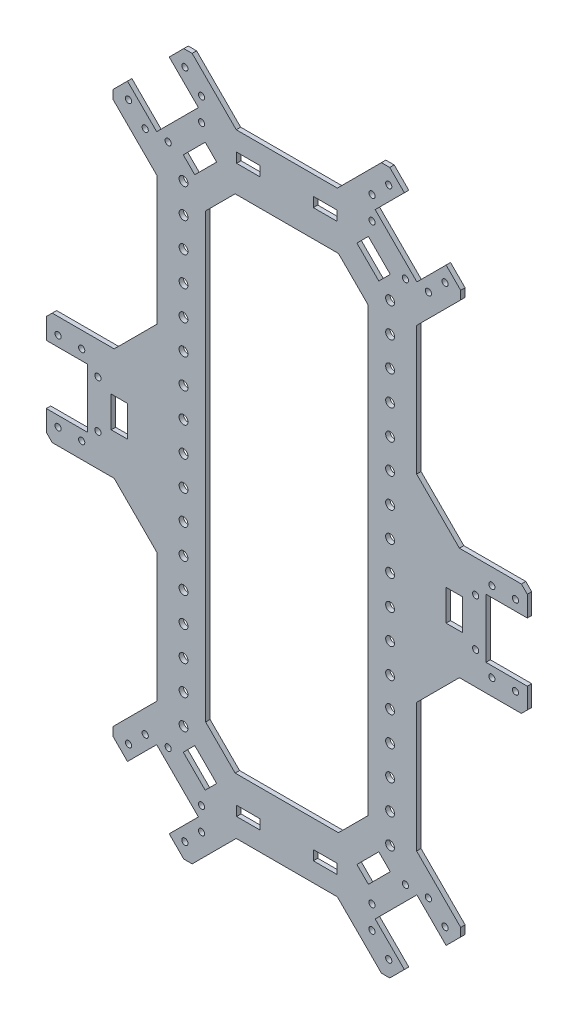
SolidWorks part; units mm, degrees
ref_plane "Спереди" through (0, 0, 0) normal (0, 0, 1) x (1, 0, 0)
ref_plane "Сверху" through (0, 0, 0) normal (0, 1, 0) x (1, 0, 0)
ref_plane "Справа" through (0, 0, 0) normal (1, 0, 0) x (0, 0, -1)
sketch "Model" plane through (0, 0, 0) normal (0, 0, 1) x (1, 0, 0)
  line L0 (-64, 8) -> (-60.95, 8) construction
  line L1 (-64, 8) -> (-67.05, 8) construction
  line L2 (-64, 8) -> (-64, 11.05) construction
  line L3 (-64, 8) -> (-64, 4.95) construction
  line L4 (-64, -8) -> (-60.95, -8) construction
  line L5 (-64, -8) -> (-67.05, -8) construction
  line L6 (-64, -8) -> (-64, -4.95) construction
  line L7 (-64, -8) -> (-64, -11.05) construction
  line L8 (-69.5, 13.5) -> (-66.45, 13.5) construction
  line L9 (-69.5, 13.5) -> (-72.55, 13.5) construction
  line L10 (-69.5, 13.5) -> (-69.5, 16.55) construction
  line L11 (-69.5, 13.5) -> (-69.5, 10.45) construction
  line L12 (-69.5, -13.5) -> (-66.45, -13.5) construction
  line L13 (-69.5, -13.5) -> (-72.55, -13.5) construction
  line L14 (-69.5, -13.5) -> (-69.5, -10.45) construction
  line L15 (-69.5, -13.5) -> (-69.5, -16.55) construction
  line L16 (-40.201, -88.8873) -> (-38.0443, -86.7306) construction
  line L17 (-40.201, -88.8873) -> (-42.3577, -91.044) construction
  line L18 (-40.201, -88.8873) -> (-42.3577, -86.7306) construction
  line L19 (-40.201, -88.8873) -> (-38.0443, -91.044) construction
  line L20 (-28.8873, -100.201) -> (-26.7306, -98.0443) construction
  line L21 (-28.8873, -100.201) -> (-31.044, -102.3577) construction
  line L22 (-28.8873, -100.201) -> (-31.044, -98.0443) construction
  line L23 (-28.8873, -100.201) -> (-26.7306, -102.3577) construction
  line L24 (-53.636, -94.5442) -> (-51.4794, -92.3875) construction
  line L25 (-53.636, -94.5442) -> (-55.7927, -96.7008) construction
  line L26 (-53.636, -94.5442) -> (-55.7927, -92.3875) construction
  line L27 (-53.636, -94.5442) -> (-51.4794, -96.7008) construction
  line L28 (-47.9792, -88.8873) -> (-45.8225, -86.7306) construction
  line L29 (-47.9792, -88.8873) -> (-50.1359, -91.044) construction
  line L30 (-47.9792, -88.8873) -> (-50.1359, -86.7306) construction
  line L31 (-47.9792, -88.8873) -> (-45.8225, -91.044) construction
  line L32 (-28.8873, -107.9792) -> (-26.7306, -105.8225) construction
  line L33 (-28.8873, -107.9792) -> (-31.044, -110.1359) construction
  line L34 (-28.8873, -107.9792) -> (-31.044, -105.8225) construction
  line L35 (-28.8873, -107.9792) -> (-26.7306, -110.1359) construction
  line L36 (-34.5442, -113.636) -> (-32.3875, -111.4794) construction
  line L37 (-34.5442, -113.636) -> (-36.7008, -115.7927) construction
  line L38 (-34.5442, -113.636) -> (-36.7008, -111.4794) construction
  line L39 (-34.5442, -113.636) -> (-32.3875, -115.7927) construction
  line L40 (-77.5, 13.5) -> (-74.45, 13.5) construction
  line L41 (-77.5, 13.5) -> (-80.55, 13.5) construction
  line L42 (-77.5, 13.5) -> (-77.5, 16.55) construction
  line L43 (-77.5, 13.5) -> (-77.5, 10.45) construction
  line L44 (-77.5, -13.5) -> (-74.45, -13.5) construction
  line L45 (-77.5, -13.5) -> (-80.55, -13.5) construction
  line L46 (-77.5, -13.5) -> (-77.5, -10.45) construction
  line L47 (-77.5, -13.5) -> (-77.5, -16.55) construction
  line L48 (-40.201, 88.8873) -> (-38.0443, 86.7306) construction
  line L49 (-40.201, 88.8873) -> (-42.3577, 91.044) construction
  line L50 (-40.201, 88.8873) -> (-42.3577, 86.7306) construction
  line L51 (-40.201, 88.8873) -> (-38.0443, 91.044) construction
  line L52 (-28.8873, 100.201) -> (-26.7306, 98.0443) construction
  line L53 (-28.8873, 100.201) -> (-31.044, 102.3577) construction
  line L54 (-28.8873, 100.201) -> (-31.044, 98.0443) construction
  line L55 (-28.8873, 100.201) -> (-26.7306, 102.3577) construction
  line L56 (-53.636, 94.5442) -> (-51.4794, 92.3875) construction
  line L57 (-53.636, 94.5442) -> (-55.7927, 96.7008) construction
  line L58 (-53.636, 94.5442) -> (-55.7927, 92.3875) construction
  line L59 (-53.636, 94.5442) -> (-51.4794, 96.7008) construction
  line L60 (-47.9792, 88.8873) -> (-45.8225, 86.7306) construction
  line L61 (-47.9792, 88.8873) -> (-50.1359, 91.044) construction
  line L62 (-47.9792, 88.8873) -> (-50.1359, 86.7306) construction
  line L63 (-47.9792, 88.8873) -> (-45.8225, 91.044) construction
  line L64 (-28.8873, 107.9792) -> (-26.7306, 105.8225) construction
  line L65 (-28.8873, 107.9792) -> (-31.044, 110.1359) construction
  line L66 (-28.8873, 107.9792) -> (-31.044, 105.8225) construction
  line L67 (-28.8873, 107.9792) -> (-26.7306, 110.1359) construction
  line L68 (-34.5442, 113.636) -> (-32.3875, 111.4794) construction
  line L69 (-34.5442, 113.636) -> (-36.7008, 115.7927) construction
  line L70 (-34.5442, 113.636) -> (-36.7008, 111.4794) construction
  line L71 (-34.5442, 113.636) -> (-32.3875, 115.7927) construction
  line L72 (64, 8) -> (60.95, 8) construction
  line L73 (64, 8) -> (67.05, 8) construction
  line L74 (64, 8) -> (64, 11.05) construction
  line L75 (64, 8) -> (64, 4.95) construction
  line L76 (64, -8) -> (60.95, -8) construction
  line L77 (64, -8) -> (67.05, -8) construction
  line L78 (64, -8) -> (64, -4.95) construction
  line L79 (64, -8) -> (64, -11.05) construction
  line L80 (69.5, 13.5) -> (66.45, 13.5) construction
  line L81 (69.5, 13.5) -> (72.55, 13.5) construction
  line L82 (69.5, 13.5) -> (69.5, 16.55) construction
  line L83 (69.5, 13.5) -> (69.5, 10.45) construction
  line L84 (69.5, -13.5) -> (66.45, -13.5) construction
  line L85 (69.5, -13.5) -> (72.55, -13.5) construction
  line L86 (69.5, -13.5) -> (69.5, -10.45) construction
  line L87 (69.5, -13.5) -> (69.5, -16.55) construction
  line L88 (40.201, -88.8873) -> (38.0443, -86.7306) construction
  line L89 (40.201, -88.8873) -> (42.3577, -91.044) construction
  line L90 (40.201, -88.8873) -> (42.3577, -86.7306) construction
  line L91 (40.201, -88.8873) -> (38.0443, -91.044) construction
  line L92 (28.8873, -100.201) -> (26.7306, -98.0443) construction
  line L93 (28.8873, -100.201) -> (31.044, -102.3577) construction
  line L94 (28.8873, -100.201) -> (31.044, -98.0443) construction
  line L95 (28.8873, -100.201) -> (26.7306, -102.3577) construction
  line L96 (53.636, -94.5442) -> (51.4794, -92.3875) construction
  line L97 (53.636, -94.5442) -> (55.7927, -96.7008) construction
  line L98 (53.636, -94.5442) -> (55.7927, -92.3875) construction
  line L99 (53.636, -94.5442) -> (51.4794, -96.7008) construction
  line L100 (47.9792, -88.8873) -> (45.8225, -86.7306) construction
  line L101 (47.9792, -88.8873) -> (50.1359, -91.044) construction
  line L102 (47.9792, -88.8873) -> (50.1359, -86.7306) construction
  line L103 (47.9792, -88.8873) -> (45.8225, -91.044) construction
  line L104 (28.8873, -107.9792) -> (26.7306, -105.8225) construction
  line L105 (28.8873, -107.9792) -> (31.044, -110.1359) construction
  line L106 (28.8873, -107.9792) -> (31.044, -105.8225) construction
  line L107 (28.8873, -107.9792) -> (26.7306, -110.1359) construction
  line L108 (34.5442, -113.636) -> (32.3875, -111.4794) construction
  line L109 (34.5442, -113.636) -> (36.7008, -115.7927) construction
  line L110 (34.5442, -113.636) -> (36.7008, -111.4794) construction
  line L111 (34.5442, -113.636) -> (32.3875, -115.7927) construction
  line L112 (77.5, 13.5) -> (74.45, 13.5) construction
  line L113 (77.5, 13.5) -> (80.55, 13.5) construction
  line L114 (77.5, 13.5) -> (77.5, 16.55) construction
  line L115 (77.5, 13.5) -> (77.5, 10.45) construction
  line L116 (77.5, -13.5) -> (74.45, -13.5) construction
  line L117 (77.5, -13.5) -> (80.55, -13.5) construction
  line L118 (77.5, -13.5) -> (77.5, -10.45) construction
  line L119 (77.5, -13.5) -> (77.5, -16.55) construction
  line L120 (40.201, 88.8873) -> (38.0443, 86.7306) construction
  line L121 (40.201, 88.8873) -> (42.3577, 91.044) construction
  line L122 (40.201, 88.8873) -> (42.3577, 86.7306) construction
  line L123 (40.201, 88.8873) -> (38.0443, 91.044) construction
  line L124 (28.8873, 100.201) -> (26.7306, 98.0443) construction
  line L125 (28.8873, 100.201) -> (31.044, 102.3577) construction
  line L126 (28.8873, 100.201) -> (31.044, 98.0443) construction
  line L127 (28.8873, 100.201) -> (26.7306, 102.3577) construction
  line L128 (53.636, 94.5442) -> (51.4794, 92.3875) construction
  line L129 (53.636, 94.5442) -> (55.7927, 96.7008) construction
  line L130 (53.636, 94.5442) -> (55.7927, 92.3875) construction
  line L131 (53.636, 94.5442) -> (51.4794, 96.7008) construction
  line L132 (47.9792, 88.8873) -> (45.8225, 86.7306) construction
  line L133 (47.9792, 88.8873) -> (50.1359, 91.044) construction
  line L134 (47.9792, 88.8873) -> (50.1359, 86.7306) construction
  line L135 (47.9792, 88.8873) -> (45.8225, 91.044) construction
  line L136 (28.8873, 107.9792) -> (26.7306, 105.8225) construction
  line L137 (28.8873, 107.9792) -> (31.044, 110.1359) construction
  line L138 (28.8873, 107.9792) -> (31.044, 105.8225) construction
  line L139 (28.8873, 107.9792) -> (26.7306, 110.1359) construction
  line L140 (34.5442, 113.636) -> (32.3875, 111.4794) construction
  line L141 (34.5442, 113.636) -> (36.7008, 115.7927) construction
  line L142 (34.5442, 113.636) -> (36.7008, 111.4794) construction
  line L143 (34.5442, 113.636) -> (32.3875, 115.7927) construction
  line L144 (27.5, -60) -> (-27.5, -60) construction
  line L145 (-17.1299, 104) -> (17.1299, 104)
  line L146 (0, 106) -> (0, -106) construction
  line L147 (-27.5, 0) -> (-27.5, 75)
  line L148 (-17.5, 85) -> (0, 85)
  line L149 (17.5, 85) -> (0, 85)
  line L150 (-27.5, 0) -> (-27.5, -75)
  line L151 (-17.5, -85) -> (0, -85)
  line L152 (17.5, -85) -> (0, -85)
  line L153 (-17.5, -85) -> (-27.5, -75)
  line L154 (-27.5, 75) -> (-17.5, 85)
  line L155 (-67.5, 10) -> (-67.5, -10)
  line L156 (-58.5, 19) -> (-79.5, 19)
  line L157 (2, 0) -> (-69.5, 0) construction
  line L158 (-2, 0) -> (69.5, 0) construction
  line L159 (27.5, 0) -> (-27.5, 0) construction
  line L160 (-53.9896, -99.8475) -> (-44.0901, -89.948)
  line L161 (-44.0901, -89.948) -> (-29.948, -104.0901)
  line L162 (-29.948, -104.0901) -> (-39.8475, -113.9896)
  line L163 (-53.9896, -99.8475) -> (-58.9393, -94.8977)
  line L164 (-39.8475, -113.9896) -> (-34.8977, -118.9393)
  line L165 (-44, -77.1299) -> (-58.9393, -92.0693)
  line L166 (-58.9393, -94.8977) -> (-58.9393, -92.0693)
  line L167 (-17.1299, -104) -> (-32.0693, -118.9393)
  line L168 (-34.8977, -118.9393) -> (-32.0693, -118.9393)
  line L169 (-38.4332, -98.4332) -> (1.4142, -58.5858) construction
  line L170 (38.4332, -98.4332) -> (-1.4142, -58.5858) construction
  line L171 (-17.1299, -104) -> (17.1299, -104)
  line L172 (-81.5, 10) -> (-67.5, 10)
  line L173 (-67.5, -10) -> (-81.5, -10)
  line L174 (-81.5, 10) -> (-81.5, 17)
  line L175 (-81.5, -10) -> (-81.5, -17)
  line L176 (-81.5, 17) -> (-79.5, 19)
  line L177 (-81.5, -17) -> (-79.5, -19)
  line L178 (27.5, 60) -> (-27.5, 60) construction
  line L179 (-17.5, 85) -> (0, 85)
  line L180 (17.5, 85) -> (0, 85)
  line L181 (-17.5, 85) -> (-27.5, 75)
  line L182 (-53.9896, 99.8475) -> (-44.0901, 89.948)
  line L183 (-44.0901, 89.948) -> (-29.948, 104.0901)
  line L184 (-29.948, 104.0901) -> (-39.8475, 113.9896)
  line L185 (-53.9896, 99.8475) -> (-58.9393, 94.8977)
  line L186 (-39.8475, 113.9896) -> (-34.8977, 118.9393)
  line L187 (-44, 77.1299) -> (-58.9393, 92.0693)
  line L188 (-58.9393, 94.8977) -> (-58.9393, 92.0693)
  line L189 (-17.1299, 104) -> (-32.0693, 118.9393)
  line L190 (-34.8977, 118.9393) -> (-32.0693, 118.9393)
  line L191 (-38.4332, 98.4332) -> (1.4142, 58.5858) construction
  line L192 (38.4332, 98.4332) -> (-1.4142, 58.5858) construction
  line L193 (-17.1299, 104) -> (17.1299, 104)
  line L194 (-44, 77.1299) -> (-44, 33.5)
  line L195 (-31.3622, 91.3622) -> (-27.6499, 95.0745)
  line L196 (-27.6499, 95.0745) -> (-23.7608, 91.1854)
  line L197 (-31.3622, 91.3622) -> (-35.0745, 87.6499)
  line L198 (-35.0745, 87.6499) -> (-31.1854, 83.7608)
  line L199 (-27.4731, 87.4731) -> (-23.7608, 91.1854)
  line L200 (-27.4731, 87.4731) -> (-31.1854, 83.7608)
  line L201 (-31.3622, -91.3622) -> (-27.6499, -95.0745)
  line L202 (-27.6499, -95.0745) -> (-23.7608, -91.1854)
  line L203 (-31.3622, -91.3622) -> (-35.0745, -87.6499)
  line L204 (-35.0745, -87.6499) -> (-31.1854, -83.7608)
  line L205 (-27.4731, -87.4731) -> (-23.7608, -91.1854)
  line L206 (-27.4731, -87.4731) -> (-31.1854, -83.7608)
  line L207 (-59.5, 0) -> (-59.5, -5.25)
  line L208 (-59.5, -5.25) -> (-54, -5.25)
  line L209 (-59.5, 0) -> (-59.5, 5.25)
  line L210 (-59.5, 5.25) -> (-54, 5.25)
  line L211 (-54, 0) -> (-54, -5.25)
  line L212 (-54, 0) -> (-54, 5.25)
  line L213 (-35, 82) -> (-35, -2) construction
  line L214 (-35, -82) -> (-35, 2) construction
  line L215 (-17, 94.2) -> (-17, 97.5)
  line L216 (-17, 97.5) -> (-9, 97.5)
  line L217 (-9, 97.5) -> (-9, 94.2)
  line L218 (-17, 94.2) -> (-9, 94.2)
  line L219 (17, 97.5) -> (9, 97.5)
  line L220 (9, 97.5) -> (9, 94.2)
  line L221 (17, 94.2) -> (9, 94.2)
  line L222 (-17, -94.2) -> (-17, -97.5)
  line L223 (-17, -97.5) -> (-9, -97.5)
  line L224 (-9, -97.5) -> (-9, -94.2)
  line L225 (-17, -94.2) -> (-9, -94.2)
  line L226 (17, -97.5) -> (9, -97.5)
  line L227 (9, -97.5) -> (9, -94.2)
  line L228 (17, -94.2) -> (9, -94.2)
  line L229 (-58.5, 19) -> (-44, 33.5)
  line L230 (-58.5, -19) -> (-79.5, -19)
  line L231 (-44, -77.1299) -> (-44, -33.5)
  line L232 (-58.5, -19) -> (-44, -33.5)
  line L233 (27.5, 0) -> (27.5, 75)
  line L234 (27.5, 0) -> (27.5, -75)
  line L235 (17.5, -85) -> (27.5, -75)
  line L236 (27.5, 75) -> (17.5, 85)
  line L237 (67.5, 10) -> (67.5, -10)
  line L238 (58.5, 19) -> (79.5, 19)
  line L239 (53.9896, -99.8475) -> (44.0901, -89.948)
  line L240 (44.0901, -89.948) -> (29.948, -104.0901)
  line L241 (29.948, -104.0901) -> (39.8475, -113.9896)
  line L242 (53.9896, -99.8475) -> (58.9393, -94.8977)
  line L243 (39.8475, -113.9896) -> (34.8977, -118.9393)
  line L244 (44, -77.1299) -> (58.9393, -92.0693)
  line L245 (58.9393, -94.8977) -> (58.9393, -92.0693)
  line L246 (17.1299, -104) -> (32.0693, -118.9393)
  line L247 (34.8977, -118.9393) -> (32.0693, -118.9393)
  line L248 (81.5, 10) -> (67.5, 10)
  line L249 (67.5, -10) -> (81.5, -10)
  line L250 (81.5, 10) -> (81.5, 17)
  line L251 (81.5, -10) -> (81.5, -17)
  line L252 (81.5, 17) -> (79.5, 19)
  line L253 (81.5, -17) -> (79.5, -19)
  line L254 (17.5, 85) -> (27.5, 75)
  line L255 (53.9896, 99.8475) -> (44.0901, 89.948)
  line L256 (44.0901, 89.948) -> (29.948, 104.0901)
  line L257 (29.948, 104.0901) -> (39.8475, 113.9896)
  line L258 (53.9896, 99.8475) -> (58.9393, 94.8977)
  line L259 (39.8475, 113.9896) -> (34.8977, 118.9393)
  line L260 (44, 77.1299) -> (58.9393, 92.0693)
  line L261 (58.9393, 94.8977) -> (58.9393, 92.0693)
  line L262 (17.1299, 104) -> (32.0693, 118.9393)
  line L263 (34.8977, 118.9393) -> (32.0693, 118.9393)
  line L264 (44, 77.1299) -> (44, 33.5)
  line L265 (31.3622, 91.3622) -> (27.6499, 95.0745)
  line L266 (27.6499, 95.0745) -> (23.7608, 91.1854)
  line L267 (31.3622, 91.3622) -> (35.0745, 87.6499)
  line L268 (35.0745, 87.6499) -> (31.1854, 83.7608)
  line L269 (27.4731, 87.4731) -> (23.7608, 91.1854)
  line L270 (27.4731, 87.4731) -> (31.1854, 83.7608)
  line L271 (31.3622, -91.3622) -> (27.6499, -95.0745)
  line L272 (27.6499, -95.0745) -> (23.7608, -91.1854)
  line L273 (31.3622, -91.3622) -> (35.0745, -87.6499)
  line L274 (35.0745, -87.6499) -> (31.1854, -83.7608)
  line L275 (27.4731, -87.4731) -> (23.7608, -91.1854)
  line L276 (27.4731, -87.4731) -> (31.1854, -83.7608)
  line L277 (59.5, 0) -> (59.5, -5.25)
  line L278 (59.5, -5.25) -> (54, -5.25)
  line L279 (59.5, 0) -> (59.5, 5.25)
  line L280 (59.5, 5.25) -> (54, 5.25)
  line L281 (54, 0) -> (54, -5.25)
  line L282 (54, 0) -> (54, 5.25)
  line L283 (35, 82) -> (35, -2) construction
  line L284 (35, -82) -> (35, 2) construction
  line L285 (17, 94.2) -> (17, 97.5)
  line L286 (17, -94.2) -> (17, -97.5)
  line L287 (58.5, 19) -> (44, 33.5)
  line L288 (58.5, -19) -> (79.5, -19)
  line L289 (44, -77.1299) -> (44, -33.5)
  line L290 (58.5, -19) -> (44, -33.5)
  circle A0 centre (-64, 8) radius 1.05
  circle A1 centre (-64, -8) radius 1.05
  circle A2 centre (-77.5, 13.5) radius 1.05
  circle A3 centre (-69.5, 13.5) radius 1.05
  circle A4 centre (-77.5, -13.5) radius 1.05
  circle A5 centre (-69.5, -13.5) radius 1.05
  circle A6 centre (-40.201, -88.8873) radius 1.05
  circle A7 centre (-28.8873, -100.201) radius 1.05
  circle A8 centre (-53.636, -94.5442) radius 1.05
  circle A9 centre (-47.9792, -88.8873) radius 1.05
  circle A10 centre (-34.5442, -113.636) radius 1.05
  circle A11 centre (-28.8873, -107.9792) radius 1.05
  circle A12 centre (-40.201, 88.8873) radius 1.05
  circle A13 centre (-28.8873, 100.201) radius 1.05
  circle A14 centre (-53.636, 94.5442) radius 1.05
  circle A15 centre (-47.9792, 88.8873) radius 1.05
  circle A16 centre (-34.5442, 113.636) radius 1.05
  circle A17 centre (-28.8873, 107.9792) radius 1.05
  circle A18 centre (-35, 0) radius 1.5
  circle A19 centre (-35, 10) radius 1.5
  circle A20 centre (-35, 20) radius 1.5
  circle A21 centre (-35, 30) radius 1.5
  circle A22 centre (-35, 40) radius 1.5
  circle A23 centre (-35, 50) radius 1.5
  circle A24 centre (-35, 60) radius 1.5
  circle A25 centre (-35, 70) radius 1.5
  circle A26 centre (-35, 80) radius 1.5
  circle A27 centre (-35, -10) radius 1.5
  circle A28 centre (-35, -20) radius 1.5
  circle A29 centre (-35, -30) radius 1.5
  circle A30 centre (-35, -40) radius 1.5
  circle A31 centre (-35, -50) radius 1.5
  circle A32 centre (-35, -60) radius 1.5
  circle A33 centre (-35, -70) radius 1.5
  circle A34 centre (-35, -80) radius 1.5
  circle A35 centre (64, 8) radius 1.05
  circle A36 centre (64, -8) radius 1.05
  circle A37 centre (77.5, 13.5) radius 1.05
  circle A38 centre (69.5, 13.5) radius 1.05
  circle A39 centre (77.5, -13.5) radius 1.05
  circle A40 centre (69.5, -13.5) radius 1.05
  circle A41 centre (40.201, -88.8873) radius 1.05
  circle A42 centre (28.8873, -100.201) radius 1.05
  circle A43 centre (53.636, -94.5442) radius 1.05
  circle A44 centre (47.9792, -88.8873) radius 1.05
  circle A45 centre (34.5442, -113.636) radius 1.05
  circle A46 centre (28.8873, -107.9792) radius 1.05
  circle A47 centre (40.201, 88.8873) radius 1.05
  circle A48 centre (28.8873, 100.201) radius 1.05
  circle A49 centre (53.636, 94.5442) radius 1.05
  circle A50 centre (47.9792, 88.8873) radius 1.05
  circle A51 centre (34.5442, 113.636) radius 1.05
  circle A52 centre (28.8873, 107.9792) radius 1.05
  circle A53 centre (35, 0) radius 1.5
  circle A54 centre (35, 10) radius 1.5
  circle A55 centre (35, 20) radius 1.5
  circle A56 centre (35, 30) radius 1.5
  circle A57 centre (35, 40) radius 1.5
  circle A58 centre (35, 50) radius 1.5
  circle A59 centre (35, 60) radius 1.5
  circle A60 centre (35, 70) radius 1.5
  circle A61 centre (35, 80) radius 1.5
  circle A62 centre (35, -10) radius 1.5
  circle A63 centre (35, -20) radius 1.5
  circle A64 centre (35, -30) radius 1.5
  circle A65 centre (35, -40) radius 1.5
  circle A66 centre (35, -50) radius 1.5
  circle A67 centre (35, -60) radius 1.5
  circle A68 centre (35, -70) radius 1.5
  circle A69 centre (35, -80) radius 1.5
extrude "Бобышка-Вытянуть1" add sketch "Model" along normal blind 1.5 contours L290 L288 L253 L251 L249 L237 L248 L250 L252 L238 L287 L264 L260 L261 L258 L255 L256 L257 L259 L263 L262 L145 L189 L190 L186 L184 L183 L182 L185 L188 L187 L194 L229 L156 L176 L174 L172 L155 L173 L175 L177 L230 L232 L231 L165 L166 L163 L160 L161 L162 L164
